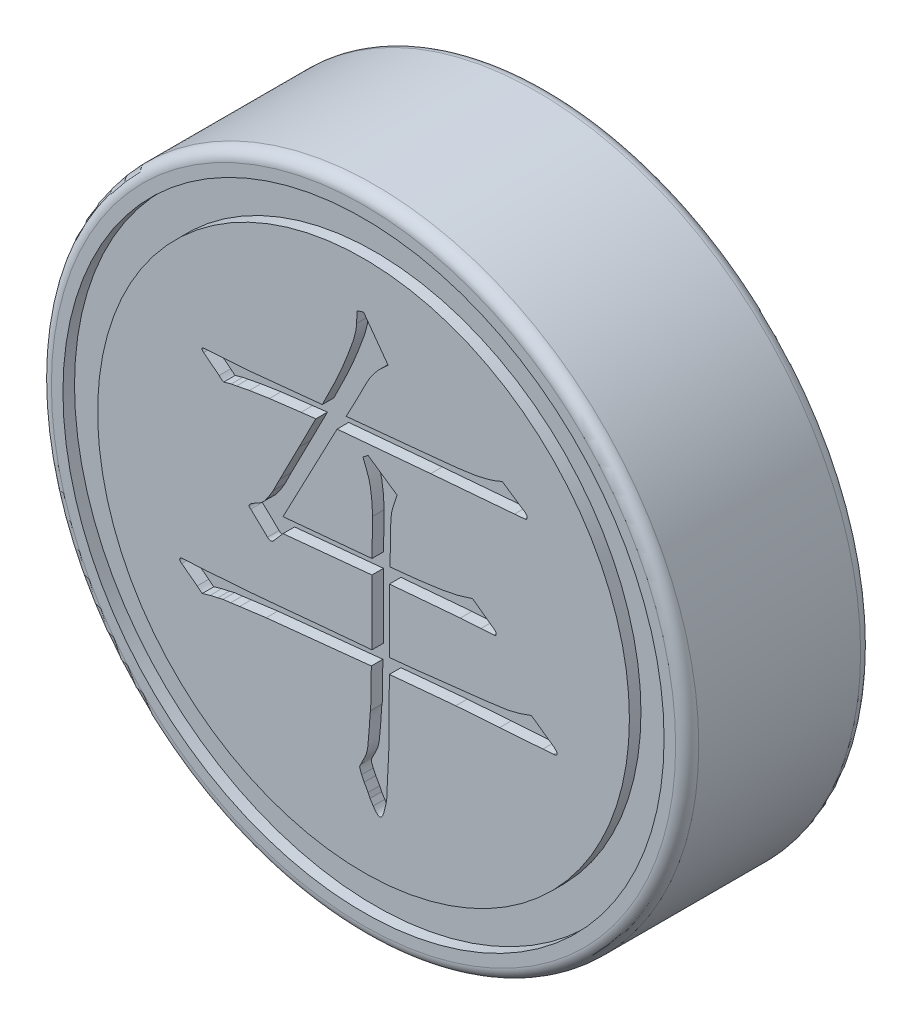
SolidWorks part; units mm, degrees
ref_plane "前视基准面" through (0, 0, 0) normal (0, 0, 1) x (1, 0, 0)
ref_plane "上视基准面" through (0, 0, 0) normal (0, 1, 0) x (1, 0, 0)
ref_plane "右视基准面" through (0, 0, 0) normal (1, 0, 0) x (0, 0, -1)
sketch "草图1" plane through (0, 0, 0) normal (0, 0, 1) x (1, 0, 0)
  circle A0 centre (0, 0) radius 14
extrude "凸台-拉伸1" add sketch "草图1" along normal blind 8
sketch "草图2" plane through (0, 0, 8) normal (0, 0, 1) x (1, 0, 0)
  circle A0 centre (0, 0) radius 13
  circle A1 centre (0, 0) radius 11.5
extrude "切除-拉伸1" cut sketch "草图2" against normal blind 0.5
sketch "草图3" plane through (0, 0, 0) normal (0, 0, -1) x (-1, 0, 0)
  circle A0 centre (0, 0) radius 5.1
extrude "切除-拉伸2" cut sketch "草图3" against normal blind 5
chamfer "倒角1" distance 0.5 angle 45 1 edges at (-5.1, 0, 0)
fillet "圆角1" radius 0.5 2 edges at (14, 0, 8) (14, 0, 0)
sketch "草图4" plane through (0, 0, 8) normal (0, 0, 1) x (1, 0, 0)
  text T0 "车" font "汉仪长仿宋体" height 13
extrude "切除-拉伸3" cut sketch "草图4" against normal blind 0.5
